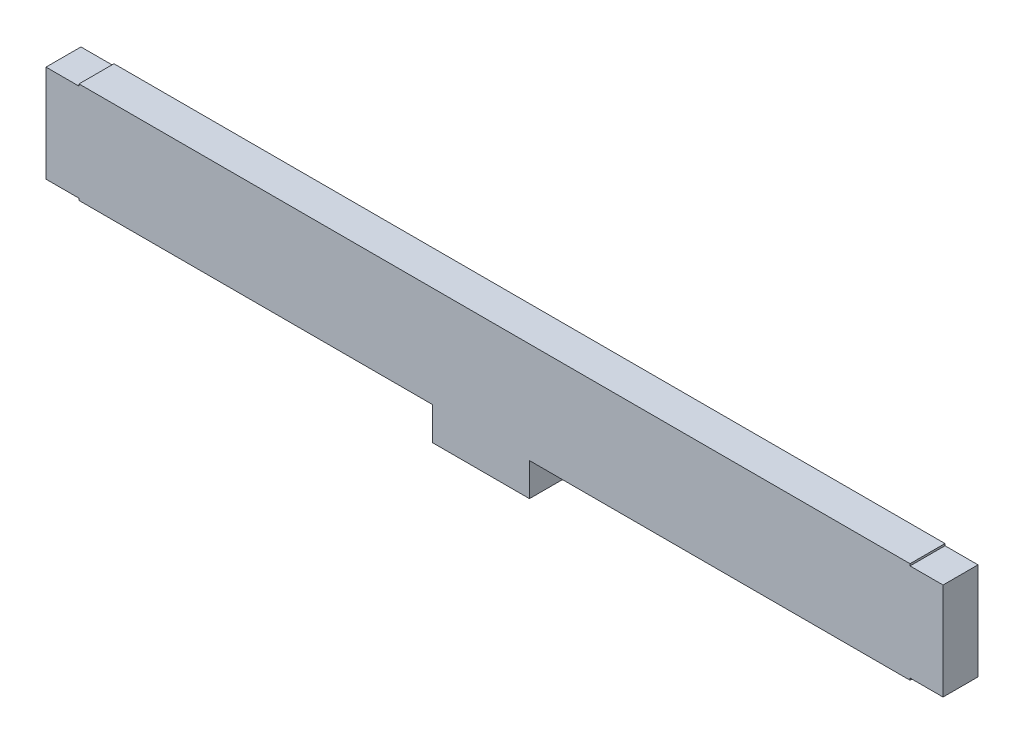
SolidWorks part; units mm, degrees
material "Maple"
ref_plane "Front Plane" through (0, 0, 0) normal (0, 0, 1) x (1, 0, 0)
ref_plane "Top Plane" through (0, 0, 0) normal (0, 1, 0) x (1, 0, 0)
ref_plane "Right Plane" through (0, 0, 0) normal (1, 0, 0) x (0, 0, -1)
sketch "Sketch1" plane through (0, 0, 0) normal (0, 0, 1) x (1, 0, 0)
  line L0 (214, 0) -> (214, -45) construction
  line L1 (0, 0) -> (428, 0)
  line L2 (0, 0) -> (0, -1)
  line L4 (428, 0) -> (428, -1)
  line L5 (546, -45) -> (214, -45) construction
  line L16 (0, -51) -> (0, -52)
  line L17 (-17, -1) -> (0, -1)
  line L22 (-17, -1) -> (-17, -51)
  line L23 (-17, -51) -> (0, -51)
  line L27 (445, -51) -> (428, -51)
  line L28 (445, -1) -> (445, -51)
  line L29 (445, -1) -> (428, -1)
  line L30 (428, -51) -> (428, -52)
  line L43 (428, -52) -> (232, -52)
  line L44 (182, -52) -> (0, -52)
  line L46 (182, -52) -> (182, -69)
  line L47 (182, -69) -> (232, -69)
  line L48 (232, -52) -> (232, -69)
  point P10 (9, -45)
  point P12 (0, 0)
  point P13 (214, -90)
  dimension "D1" = 428
  dimension "D2" = 52
  dimension "D3" = 50
  dimension "D4" = 50
  dimension "D5" = 182
  dimension "D6" = 1
extrude "Boss-Extrude1" add sketch "Sketch1" along normal blind 18
